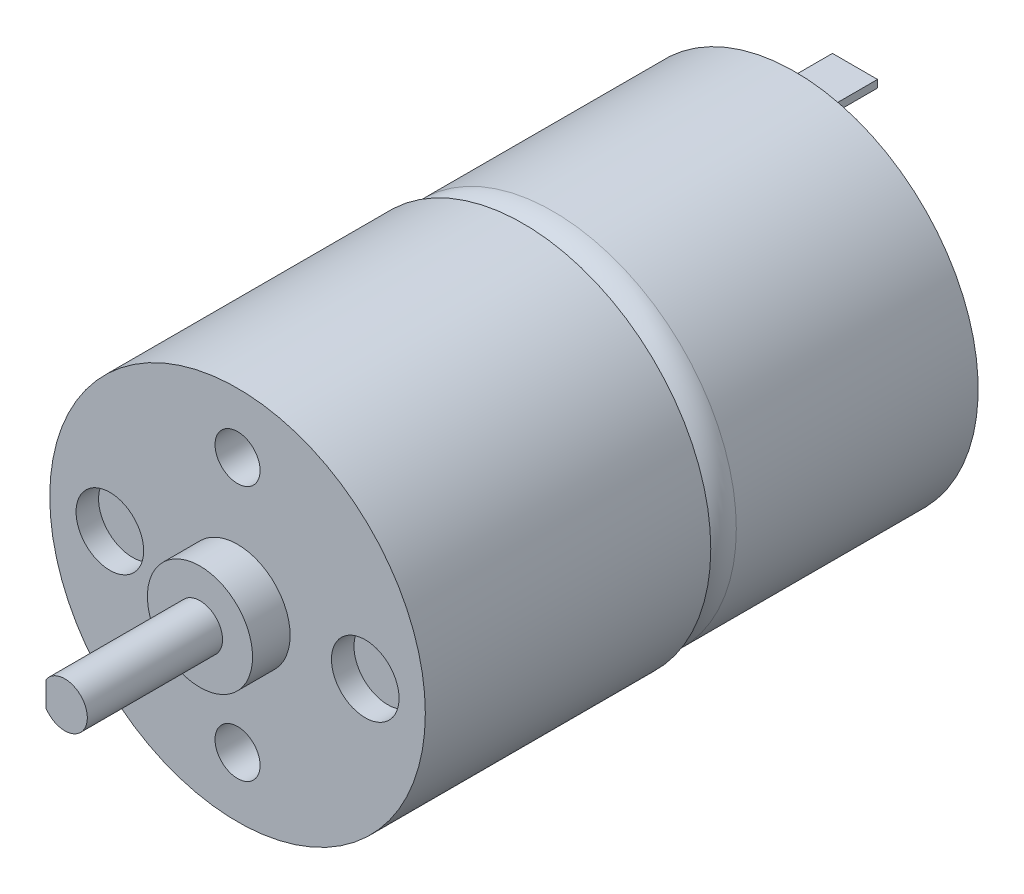
SolidWorks part; units mm, degrees
ref_plane "前视基准面" through (0, 0, 0) normal (0, 0, 1) x (1, 0, 0)
ref_plane "上视基准面" through (0, 0, 0) normal (0, 1, 0) x (1, 0, 0)
ref_plane "右视基准面" through (0, 0, 0) normal (1, 0, 0) x (0, 0, -1)
sketch "草图1" plane through (0, 0, 0) normal (0, 0, 1) x (1, 0, 0)
  circle A0 centre (0, 0) radius 12.2
  dimension "D1" = 24.4
extrude "凸台-拉伸1" add sketch "草图1" along normal blind 18.1
fillet "圆角1" radius 2 1 edges at (12.2, 0, 18.1)
sketch "草图2" plane through (0, 0, 18.1) normal (0, 0, 1) x (1, 0, 0)
  circle A0 centre (0, 0) radius 12.5
  dimension "D1" = 25
extrude "凸台-拉伸2" add sketch "草图2" along normal blind 19
sketch "草图3" plane through (0, 0, 37.1) normal (0, 0, 1) x (1, 0, 0)
  circle A0 centre (0, 0) radius 3.5
  dimension "D1" = 7
extrude "凸台-拉伸3" add sketch "草图3" along normal blind 2.5
sketch "草图4" plane through (0, 0, 39.6) normal (0, 0, 1) x (1, 0, 0)
  circle A0 centre (0, 0) radius 1.5
  dimension "D1" = 3
extrude "凸台-拉伸4" add sketch "草图4" along normal blind 9
sketch "草图5" plane through (0, 0, 48.6) normal (0, 0, 1) x (1, 0, 0)
  line L0 (-1.25, -0.8292) -> (-1.25, 0.8292)
  circle A0 centre (0, 0) radius 1.5
  circle M1 centre (0, 0) radius 1.5
  dimension "D1" = 3
  dimension "D2" = 2.75
extrude "切除-拉伸1" cut sketch "草图5" against normal blind 8 contours L0 M1
sketch "草图6" plane through (0, 0, 37.1) normal (0, 0, 1) x (1, 0, 0)
  circle A0 centre (0, 0) radius 8.5 construction
  circle A1 centre (8.5, 0) radius 2.25
  circle A2 centre (-8.5, 0) radius 2.25
  dimension "D1" = 17
  dimension "D2" = 4.5
  dimension "D3" = 4.5
extrude "切除-拉伸2" cut sketch "草图6" against normal blind 1.5
sketch "草图8" plane through (0, 0, 37.1) normal (0, 0, 1) x (1, 0, 0)
  circle A0 centre (0, 0) radius 8.5 construction
  circle A1 centre (0, 8.5) radius 1.5
  circle A2 centre (0, -8.5) radius 1.5
  dimension "D1" = 17
  dimension "D2" = 3
  dimension "D3" = 3
extrude "切除-拉伸3" cut sketch "草图8" against normal blind 6
sketch "草图9" plane through (0, 0, 0) normal (0, 0, -1) x (-1, 0, 0)
  circle A0 centre (0, 0) radius 3.25
  dimension "D1" = 6.5
extrude "凸台-拉伸5" add sketch "草图9" along normal blind 2
sketch "草图10" plane through (0, 0, 0) normal (0, 0, -1) x (-1, 0, 0)
  line L0 (0, 10) -> (0, 0) construction
  line L1 (-1.5, 10.5) -> (1.5, 10.5)
  line L2 (-1.5, 10.5) -> (-1.5, 10)
  line L3 (-1.5, 10) -> (1.5, 10)
  line L4 (1.5, 10.5) -> (1.5, 10)
  line L5 (-1.5, -10) -> (1.5, -10)
  line L6 (-1.5, -10) -> (-1.5, -10.5)
  line L7 (-1.5, -10.5) -> (1.5, -10.5)
  line L8 (1.5, -10) -> (1.5, -10.5)
  line L9 (0, 0) -> (0, -10) construction
  line L10 (0, 0) -> (5.9339, 0) construction
  dimension "D1" = 0.5
  dimension "D2" = 0.5
  dimension "D3" = 3
  dimension "D4" = 10
extrude "凸台-拉伸6" add sketch "草图10" along normal blind 4
